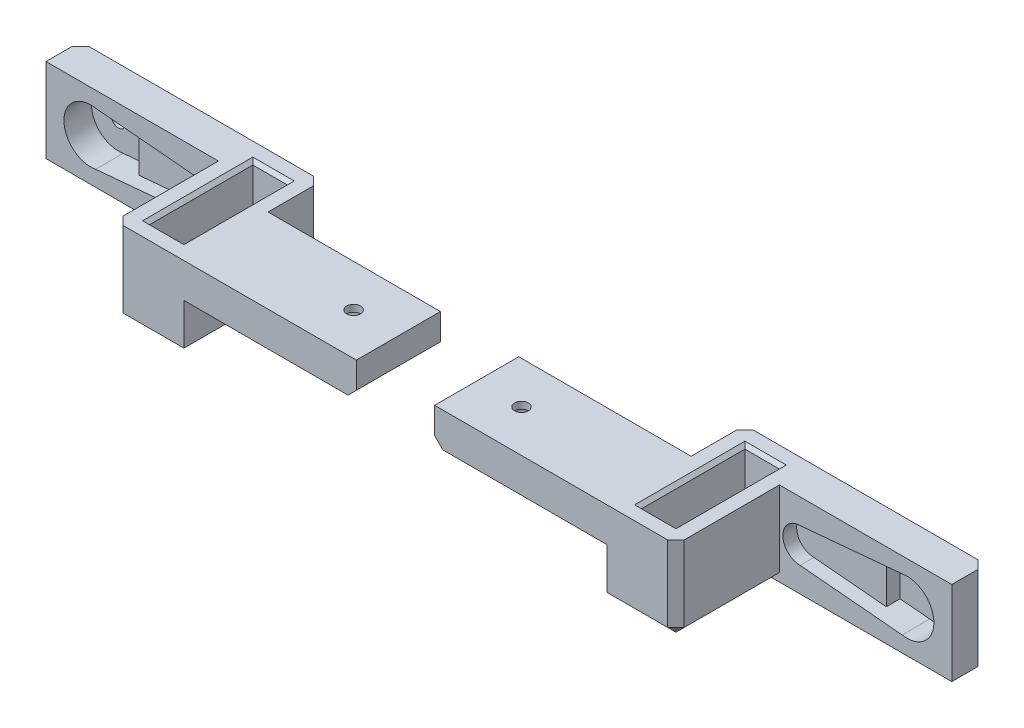
SolidWorks part; units mm, degrees
ref_plane "Front Plane" through (0, 0, 0) normal (0, 0, 1) x (1, 0, 0)
ref_plane "Top Plane" through (0, 0, 0) normal (0, 1, 0) x (1, 0, 0)
ref_plane "Right Plane" through (0, 0, 0) normal (1, 0, 0) x (0, 0, -1)
sketch "Sketch1" plane through (0, 0, 0) normal (0, 0, 1) x (1, 0, 0)
  line L1 (-35.5488, 11.7605) -> (-0.5488, 11.7605)
  line L2 (-35.5488, 11.7605) -> (-35.5488, -0.4395)
  line L3 (-35.5488, -0.4395) -> (-0.5488, -0.4395)
  line L4 (-0.5488, 11.7605) -> (-0.5488, -0.4395)
  dimension "D1" = 35
  dimension "D2" = 12.2
extrude "Boss-Extrude1" add sketch "Sketch1" along normal blind 5
sketch "Sketch2" plane through (0, 0, 5) normal (0, 0, 1) x (1, 0, 0)
  line L0 (-0.5488, 11.7605) -> (-35.5488, 11.7605) construction
  line L3 (-35.5488, 11.7605) -> (-35.5488, -0.4395) construction
  circle A0 centre (-29.0488, 5.6605) radius 1
  dimension "D1" = 2
  dimension "D2" = 6.1
  dimension "D3" = 6.5
extrude "Cut-Extrude1" cut sketch "Sketch2" against normal through all contours A0
sketch "Sketch3" plane through (0, 0, 5) normal (0, 0, 1) x (1, 0, 0)
  line L0 (-35.5488, -0.4395) -> (-0.5488, -0.4395) construction
  line L1 (-0.5488, 11.7605) -> (-10.5488, 11.7605)
  line L2 (-0.5488, 11.7605) -> (-0.5488, -0.4395)
  line L3 (-0.5488, -0.4395) -> (-10.5488, -0.4395)
  line L4 (-10.5488, 11.7605) -> (-10.5488, -0.4395)
  dimension "D1" = 10
extrude "Boss-Extrude2" add sketch "Sketch3" along normal blind 15
sketch "Sketch4" plane through (-0.5488, 0, 0) normal (1, 0, 0) x (0, 0, -1)
  line L1 (-20, 11.7605) -> (-7.8, 11.7605)
  line L2 (-20, 11.7605) -> (-20, 6.7605)
  line L3 (-20, 6.7605) -> (-7.8, 6.7605)
  line L4 (-7.8, 11.7605) -> (-7.8, 6.7605)
  dimension "D1" = 12.2
  dimension "D2" = 5
  dimension "D3" = 12.2
extrude "Boss-Extrude3" add sketch "Sketch4" along normal blind 25 contours L2 L1 L4 L3
sketch "Sketch5" plane through (0, 6.7605, 0) normal (0, -1, 0) x (1, 0, 0)
  line L0 (24.4512, 20) -> (24.4512, 7.8) construction
  line L1 (24.4512, 20) -> (-0.5488, 20) construction
  circle A0 centre (17.9512, 13.9) radius 1
  dimension "D3" = 2
  dimension "D1" = 6.5
  dimension "D2" = 6.1
extrude "Cut-Extrude2" cut sketch "Sketch5" against normal through all and the other way through all contours A0
sketch "Sketch7" plane through (0, 0, 0) normal (0, 0, -1) x (-1, 0, 0)
  line L0 (0.5488, 11.7605) -> (35.5488, 11.7605) construction
  line L1 (23.0488, 5.6605) -> (19.2988, 7.8256)
  line L2 (19.2988, 7.8256) -> (19.2988, 3.4954)
  line L3 (19.2988, 3.4954) -> (23.0488, 5.6605)
  line L5 (35.5488, 11.7605) -> (35.5488, -0.4395) construction
  circle A0 centre (20.5488, 5.6605) radius 1.25 construction
  dimension "D2" = 2.5
  dimension "D1" = 6.1
  dimension "D3" = 15
  dimension "D4" = 3.75
extrude "Cut-Extrude3" cut sketch "Sketch7" against normal blind 0.5
chamfer "Chamfer1" distance 1.2 angle 45 10 edges at (24.4512, 6.7605, 13.9) (-35.5488, 5.6605, 0) (-0.5488, 3.1605, 20) (-0.5488, 5.6605, 0) (-10.5488, -0.4395, 12.5) (-10.5488, 11.7605, 12.5) (-5.5488, -0.4395, 20) (-10.5488, 5.6605, 20) (-18.0488, -0.4395, 0) (-0.5488, -0.4395, 10)
sketch "Sketch8" plane through (0, 0, 5) normal (0, 0, 1) x (1, 0, 0)
  circle A0 centre (-29.0488, 5.6605) radius 3.9
  dimension "D1" = 7.8
extrude "Cut-Extrude4" cut sketch "Sketch8" against normal blind 4
sketch "Sketch10" plane through (0, 0, 5) normal (0, 0, 1) x (1, 0, 0)
  line L0 (-29.0488, 5.6605) -> (-11.0488, 5.6605) construction
  line L1 (-29.0488, 5.6605) -> (-24.0488, 5.6605) construction
  line L2 (-11.0488, 5.6605) -> (-13.5488, 5.6605) construction
  line L3 (-29.0488, 9.5605) -> (-13.5488, 8.1605)
  line L5 (-13.5488, 3.1605) -> (-29.0488, 1.7605)
  line L6 (-29.0488, 1.7605) -> (-29.0488, 9.5605)
  arc A0 (-13.5488, 3.1605) -> (-13.5488, 8.1605) centre (-13.5488, 5.6605) ccw
  circle A1 centre (-29.0488, 5.6605) radius 3.9 construction
  circle A2 centre (-29.0488, 5.6605) radius 3.9 construction
  dimension "D1" = 18
  dimension "D2" = 2.5
  dimension "D3" = 7.8
extrude "Cut-Extrude5" cut sketch "Sketch10" against normal blind 2
sketch "Sketch12" plane through (0, 0, 5) normal (0, 0, 1) x (1, 0, 0)
  line L0 (-24.0488, 5.6605) -> (-24.0488, 9.1089)
  line L1 (-29.0488, 9.5605) -> (-13.5488, 8.1605) construction
  line L2 (-24.0488, 9.1089) -> (-29.0488, 9.5605)
  line L3 (-29.0488, 9.5605) -> (-29.0488, 1.7605)
  line L4 (-29.0488, 1.7605) -> (-24.0488, 2.2121)
  line L5 (-13.5488, 3.1605) -> (-29.0488, 1.7605) construction
  line L6 (-24.0488, 2.2121) -> (-24.0488, 5.6605)
extrude "Cut-Extrude6" cut sketch "Sketch12" against normal blind 4
sketch "Sketch20" plane through (0, 6.7605, 0) normal (0, -1, 0) x (1, 0, 0)
  circle A0 centre (17.9512, 13.9) radius 3.9
  dimension "D1" = 7.8
extrude "Cut-Extrude11" cut sketch "Sketch20" against normal blind 4
sketch "Sketch21" plane through (0, 6.7605, 0) normal (0, -1, 0) x (1, 0, 0)
  line L0 (17.9512, 13.9) -> (-0.287, 13.9) construction
  line L1 (-0.287, 13.9) -> (2.213, 13.9) construction
  line L2 (17.9512, 17.8) -> (2.213, 16.4)
  line L4 (2.213, 11.4) -> (17.9512, 10)
  line L5 (17.9512, 10) -> (17.9512, 17.8)
  arc A0 (2.213, 16.4) -> (2.213, 11.4) centre (2.213, 13.9) ccw
  circle A1 centre (17.9512, 13.9) radius 3.9 construction
  circle A2 centre (17.9512, 13.9) radius 3.9 construction
  dimension "D1" = 18.2383
  dimension "D2" = 2.5
  dimension "D3" = 7.8
extrude "Cut-Extrude12" cut sketch "Sketch21" against normal blind 2
sketch "Sketch22" plane through (0, 6.7605, 0) normal (0, -1, 0) x (1, 0, 0)
  line L0 (17.9512, 13.9) -> (12.9512, 13.9) construction
  line L1 (17.9512, 17.8) -> (17.9512, 10)
  line L2 (17.9512, 10) -> (12.9512, 10.4448)
  line L3 (2.213, 11.4) -> (17.2628, 10.0612) construction
  line L4 (12.9512, 10.4448) -> (12.9512, 17.3552)
  line L5 (17.2628, 17.7388) -> (2.213, 16.4) construction
  line L6 (12.9512, 17.3552) -> (17.9512, 17.8)
  arc A0 (17.2628, 10.0612) -> (17.2628, 17.7388) centre (17.9512, 13.9) ccw construction
  circle A1 centre (17.9512, 13.9) radius 3.9 construction
  dimension "D1" = 5
extrude "Cut-Extrude13" cut sketch "Sketch22" against normal blind 4
sketch "Sketch23" plane through (0, 11.7605, 0) normal (0, 1, 0) x (1, 0, 0)
  line L0 (-1.7488, 0) -> (-34.3488, 0) construction
  line L1 (-8.0488, -2.5) -> (-3.0488, -2.5)
  line L2 (-8.0488, -2.5) -> (-8.0488, -17.5)
  line L3 (-8.0488, -17.5) -> (-3.0488, -17.5)
  line L4 (-3.0488, -2.5) -> (-3.0488, -17.5)
  line L5 (-0.5488, -7.8) -> (-0.5488, -1.2) construction
  line L6 (-10.5488, -18.8) -> (-10.5488, -5) construction
  line L7 (24.4512, -20) -> (-9.3488, -20) construction
  dimension "D1" = 2.5
  dimension "D2" = 2.5
  dimension "D3" = 2.5
  dimension "D4" = 2.5
extrude "Cut-Extrude14" cut sketch "Sketch23" against normal through all
chamfer "Chamfer2" distance 0.5 angle 45 8 edges at (-3.0488, 11.7605, 10) (-5.5488, 11.7605, 2.5) (-5.5488, 11.7605, 17.5) (-8.0488, 11.7605, 10) (-5.5488, -0.4395, 17.5) (-3.0488, -0.4395, 10) (-5.5488, -0.4395, 2.5) (-8.0488, -0.4395, 10)
sketch "Sketch24" plane through (0, 0, 0) normal (0, 1, 0) x (1, 0, 0)
  line L0 (30.129, -23.8659) -> (30.129, 5.1435) construction
ref_plane "Plane1" through (30.129, 0, 0) normal (1, 0, 0) x (0, 0, -1)
mirror "Mirror3" about plane through (30.129, 0, 0) normal (1, 0, 0) of bodies 122
split "Split1" trim tools "Plane1" bodies to split 126 resulting bodies 127
